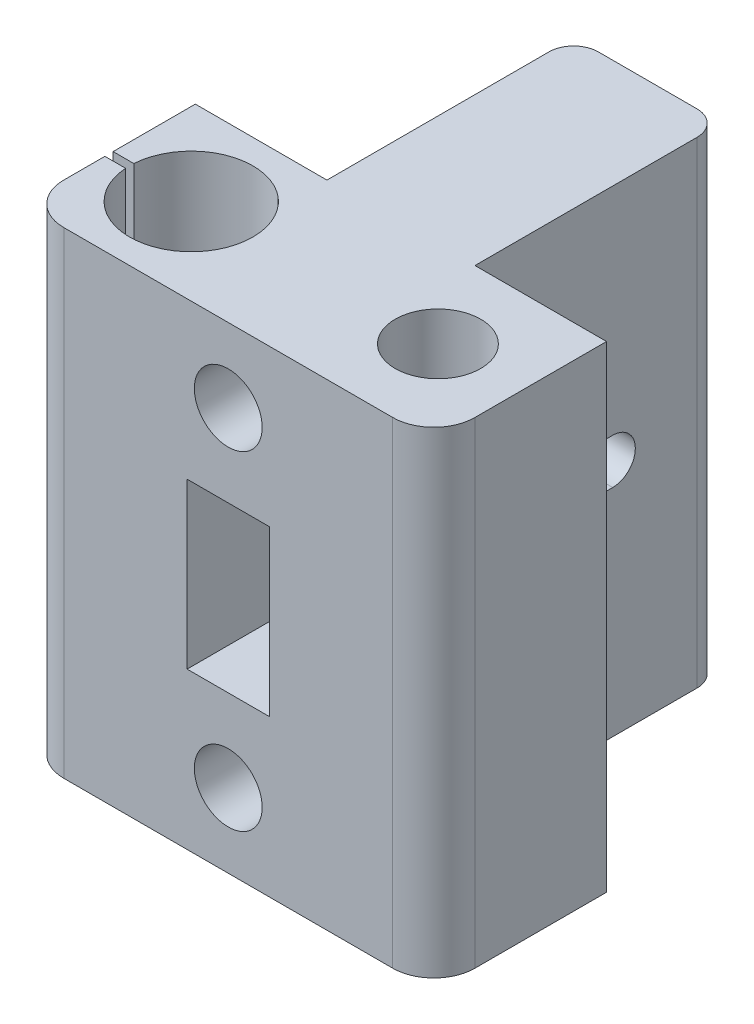
SolidWorks part; units mm, degrees
ref_plane "Front Plane" through (0, 0, 0) normal (0, 0, 1) x (1, 0, 0)
ref_plane "Top Plane" through (0, 0, 0) normal (0, 1, 0) x (1, 0, 0)
ref_plane "Right Plane" through (0, 0, 0) normal (1, 0, 0) x (0, 0, -1)
sketch "Sketch1" plane through (0, 0, 0) normal (0, 1, 0) x (1, 0, 0)
  line L1 (-25, 10.5) -> (25, 10.5)
  line L2 (-25, 10.5) -> (-25, -10.5)
  line L3 (-25, -10.5) -> (25, -10.5)
  line L4 (25, 10.5) -> (25, -10.5)
  line L5 (-25, 10.5) -> (25, -10.5) construction
  line L6 (-25, -10.5) -> (25, 10.5) construction
  point P0 (0, 0)
  dimension "D1" = 21
  dimension "D2" = 50
extrude "Boss-Extrude1" add sketch "Sketch1" along normal blind 58
sketch "Sketch3" plane through (0, 58, 0) normal (0, 1, 0) x (1, 0, 0)
  line L0 (-15, 0) -> (15, 0) construction
  circle A0 centre (-15, 0) radius 7.5
  dimension "D1" = 15
  dimension "D2" = 30
extrude "Cut-Extrude1" cut sketch "Sketch3" against normal blind 24 contours A0
sketch "Sketch4" plane through (0, 58, 0) normal (0, 1, 0) x (1, 0, 0)
  line L0 (-15, 0) -> (15, 0) construction
  circle A0 centre (15, 0) radius 5.2
  dimension "D1" = 10.4
extrude "Cut-Extrude2" cut sketch "Sketch4" against normal up to next
sketch "Sketch5" plane through (0, 0, 0) normal (0, -1, 0) x (1, 0, 0)
  circle A1 centre (-15, 0) radius 7.5
  circle A2 centre (-15, 0) radius 7.5
  dimension "D1" = 0
extrude "Cut-Extrude3" cut sketch "Sketch5" against normal blind 24
sketch "Sketch6" plane through (0, 0, 0) normal (0, -1, 0) x (1, 0, 0)
  circle A0 centre (-15, 0) radius 4.5
extrude "Cut-Extrude4" cut sketch "Sketch6" against normal up to next
sketch "Sketch8" plane through (0, 0, 10.5) normal (0, 0, 1) x (1, 0, 0)
  line L0 (-25, 29) -> (25, 29) construction
  line L1 (-25, 58) -> (-25, 0) construction
  line L2 (25, 58) -> (25, 0) construction
  line L3 (0, 58) -> (0, 0) construction
  line L4 (-25, 58) -> (25, 58) construction
  line L6 (-5, 19) -> (5, 19)
  line L7 (-5, 19) -> (-5, 39)
  line L8 (-5, 39) -> (5, 39)
  line L9 (5, 19) -> (5, 39)
  line L10 (-5, 19) -> (5, 39) construction
  line L11 (-5, 39) -> (5, 19) construction
  point P11 (0, 29)
  dimension "D1" = 20
  dimension "D2" = 10
extrude "Cut-Extrude5" cut sketch "Sketch8" against normal up to next
sketch "Sketch10" plane through (0, 0, -10.5) normal (0, 0, -1) x (-1, 0, 0)
  line L0 (-25, 29) -> (25, 29) construction
  line L1 (-25, 58) -> (-25, 0) construction
  line L2 (25, 58) -> (25, 0) construction
  line L3 (0, 58) -> (0, 0) construction
  line L4 (-25, 58) -> (25, 58) construction
sketch "Sketch11" plane through (0, 0, -10.5) normal (0, 0, -1) x (-1, 0, 0)
  line L0 (-25, 29) -> (25, 29) construction
  line L1 (9, 39) -> (5, 39)
  line L2 (9, 39) -> (9, 19)
  line L3 (9, 19) -> (5, 19)
  line L4 (5, 39) -> (5, 19)
  line L5 (9, 39) -> (5, 19) construction
  line L6 (9, 19) -> (5, 39) construction
  line L7 (0, 58) -> (0, 0) construction
  line L8 (0, 58) -> (0, 0)
  line L9 (-9, 19) -> (-5, 19)
  line L10 (-5, 39) -> (-5, 19)
  line L11 (-9, 39) -> (-5, 39)
  line L12 (-9, 39) -> (-9, 19)
  point P0 (7, 29)
  line M7 (-5, 19) -> (-5, 39)
  line M9 (5, 39) -> (5, 19)
  dimension "D1" = 5
  dimension "D2" = 4
  dimension "D3" = 20
extrude "Boss-Extrude2" add sketch "Sketch11" along normal blind 26 contours L1 L4 L3 L2 M9 | L11 L12 L9 L10 M7
sketch "Sketch12" plane through (0, 0, -36.5) normal (0, 0, -1) x (-1, 0, 0)
  line L1 (9, 19) -> (-9, 19)
  line L2 (9, 19) -> (9, 39)
  line L3 (9, 39) -> (-9, 39)
  line L4 (-9, 19) -> (-9, 39)
extrude "Boss-Extrude3" add sketch "Sketch12" along normal blind 4
sketch "Sketch13" plane through (9, 0, 0) normal (1, 0, 0) x (0, 0, -1)
  line L3 (10.5, 29) -> (40.5, 29) construction
  line L4 (10.5, 39) -> (10.5, 19) construction
  line L5 (40.5, 39) -> (40.5, 19) construction
  line L6 (18.25, 29) -> (27.25, 29) construction
  line L7 (18.25, 31.75) -> (27.25, 31.75)
  line L8 (18.25, 26.25) -> (27.25, 26.25)
  arc A0 (18.25, 31.75) -> (18.25, 26.25) centre (18.25, 29) ccw
  arc A1 (27.25, 26.25) -> (27.25, 31.75) centre (27.25, 29) ccw
  point P1 (15.5, 29)
  point P14 (22.75, 29)
  dimension "D1" = 5.5
  dimension "D2" = 5
  dimension "D3" = 9
extrude "Cut-Extrude7" cut sketch "Sketch13" against normal through all
fillet "Fillet1" radius 5 2 edges at (-25, 29, 10.5) (25, 29, 10.5)
sketch "Sketch14" plane through (0, 0, 0) normal (0, -1, 0) x (1, 0, 0)
  line L0 (20.5508, 5.5508) -> (9.4492, -5.5508) construction
  line L1 (25, -10.5) -> (-25, -10.5) construction
  circle A0 centre (20.5508, 5.5508) radius 1.95
  circle A1 centre (15, 0) radius 5.2 construction
  circle A2 centre (9.4492, -5.5508) radius 1.95
  circle A3 centre (15, 0) radius 5.2 construction
  dimension "D1" = 7.85
  dimension "D2" = 3.9
  dimension "D3" = 3.9
  dimension "D4" = 7.85
  dimension "D5" = 45
extrude "Cut-Extrude8" cut sketch "Sketch14" against normal blind 10
sketch "Sketch15" plane through (0, 58, 0) normal (0, 1, 0) x (1, 0, 0)
  line L0 (-25, 10.5) -> (-25, -5.5) construction
  line L1 (-25, -0.5) -> (-19.4721, -0.5)
  line L2 (-25, -0.5) -> (-25, 0.5)
  line L3 (-25, 0.5) -> (-19.4721, 0.5)
  line L4 (-19.4721, -0.5) -> (-19.4721, 0.5)
  circle A2 centre (-15, 0) radius 4.5 construction
  dimension "D1" = 1
extrude "Cut-Extrude9" cut sketch "Sketch15" against normal through all
sketch "Sketch17" plane through (9, 0, 0) normal (1, 0, 0) x (0, 0, -1)
  line L0 (10.5, 39) -> (10.5, 58)
  line L1 (10.5, 58) -> (40.5, 58)
  line L2 (40.5, 58) -> (40.5, 39)
  line L3 (40.5, 39) -> (10.5, 39)
  line L4 (10.5, 19) -> (10.5, 0)
  line L5 (10.5, 0) -> (40.5, 0)
  line L6 (40.5, 0) -> (40.5, 19)
  line L7 (40.5, 19) -> (10.5, 19)
extrude "Boss-Extrude5" add sketch "Sketch17" against normal up to surface (18 mm away) up to face at (-9, 29, -22.75)
sketch "Sketch7" plane through (0, 0, 10.5) normal (0, 0, 1) x (1, 0, 0)
  line L0 (0, 58) -> (0, 0) construction
  line L1 (-20, 58) -> (20, 58) construction
  line L2 (-20, 0) -> (20, 0) construction
  line L3 (-25, 29) -> (25, 29) construction
  line L4 (-25, 58) -> (-25, 0) construction
  line L5 (25, 58) -> (25, 0) construction
  circle A1 centre (0, 49) radius 4.125
  circle A2 centre (0, 9) radius 4.125
  point P24 (0, 9)
  dimension "D1" = 8.25
  dimension "D2" = 9
extrude "Cut-Extrude6" cut sketch "Sketch7" against normal blind 45
fillet "Fillet8" radius 3 2 edges at (-9, 29, -40.5) (9, 29, -40.5)
sketch "Sketch18" plane through (0, 0, -40.5) normal (0, 0, -1) x (-1, 0, 0)
  line L0 (-3, 26.25) -> (3, 26.25)
  line L1 (3, 26.25) -> (3, 31.75)
  line L2 (3, 31.75) -> (-3, 31.75)
  line L3 (-3, 31.75) -> (-3, 26.25)
  line L4 (-5, 26.25) -> (-9, 26.25) construction
  line L6 (6, 0) -> (6, 58) construction
  dimension "D1" = 5.5
  dimension "D2" = 6
  dimension "D3" = 3
extrude "Cut-Extrude10" cut sketch "Sketch18" against normal blind 1 contours L2 L3 L0 L1
